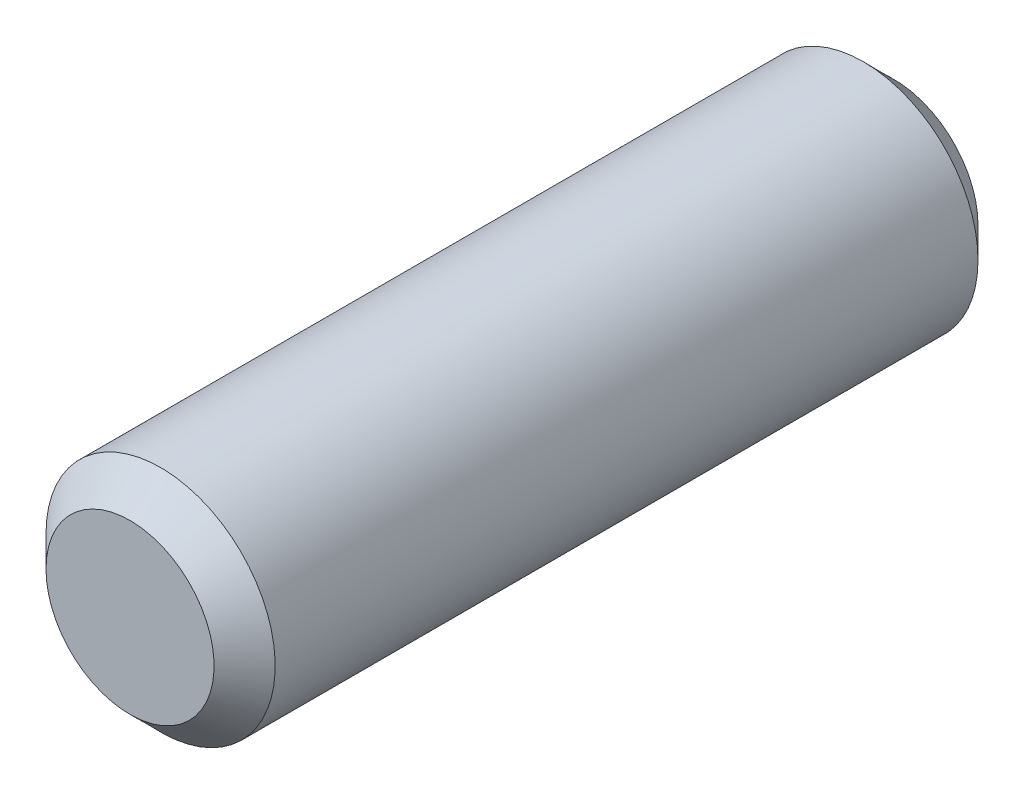
SolidWorks part; units mm, degrees
ref_plane "Front Plane" through (0, 0, 0) normal (0, 0, 1) x (1, 0, 0)
ref_plane "Top Plane" through (0, 0, 0) normal (0, 1, 0) x (1, 0, 0)
ref_plane "Right Plane" through (0, 0, 0) normal (1, 0, 0) x (0, 0, -1)
sketch "Sketch1" plane through (0, 0, 0) normal (0, 0, 1) x (1, 0, 0)
  circle A0 centre (0, 0) radius 1.5
  dimension "D1" = 3
extrude "Boss-Extrude1" add sketch "Sketch1" along normal blind 10
chamfer "Chamfer1" distance 0.4 angle 45 2 edges at (1.5, 0, 0) (1.5, 0, 10)
